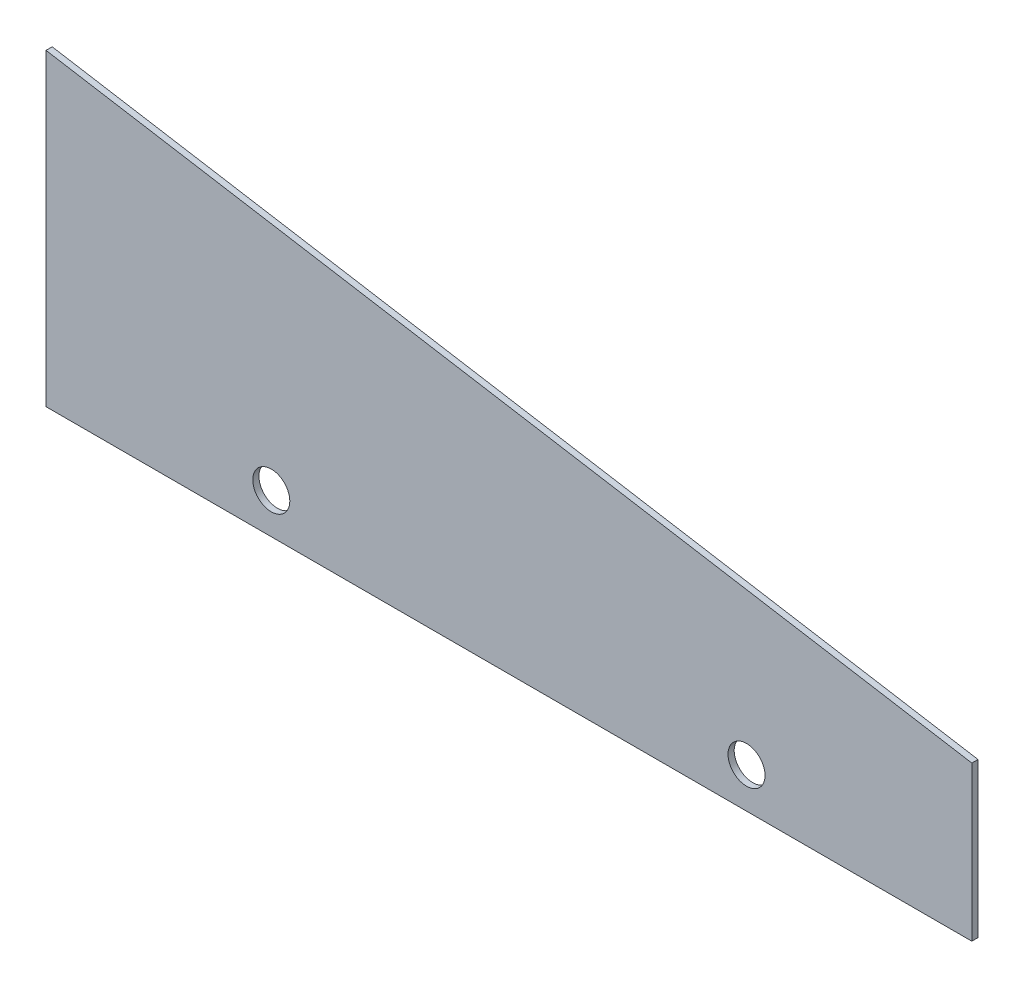
SolidWorks part; units mm, degrees
ref_plane "Alzado" through (0, 0, 0) normal (0, 0, 1) x (1, 0, 0)
ref_plane "Planta" through (0, 0, 0) normal (0, 1, 0) x (1, 0, 0)
ref_plane "Vista lateral" through (0, 0, 0) normal (1, 0, 0) x (0, 0, -1)
sketch "Croquis1" plane through (0, 0, 0) normal (0, 0, 1) x (1, 0, 0)
  line L0 (150, 0) -> (-150, 0)
  line L1 (-150, 0) -> (-150, 100)
  line L2 (-150, 100) -> (150, 50)
  line L3 (150, 50) -> (150, 0)
  dimension "D1" = 50
  dimension "D2" = 300
  dimension "D3" = 100
  dimension "D4" = 150
extrude "Saliente-Extruir1" add sketch "Croquis1" along normal blind 2
sketch "Croquis2" plane through (0, 0, 2) normal (0, 0, 1) x (1, 0, 0)
  line L0 (-150, 100) -> (-150, 0) construction
  line L1 (-150, 0) -> (150, 0) construction
  line L2 (150, 0) -> (150, 50) construction
  circle A0 centre (-77, 13) radius 6
  circle A1 centre (77, 13) radius 6
  dimension "D1" = 12
  dimension "D3" = 13
  dimension "D4" = 12
  dimension "D5" = 73
  dimension "D6" = 13
  dimension "D2" = 73
extrude "Cortar-Extruir1" cut sketch "Croquis2" against normal through all
